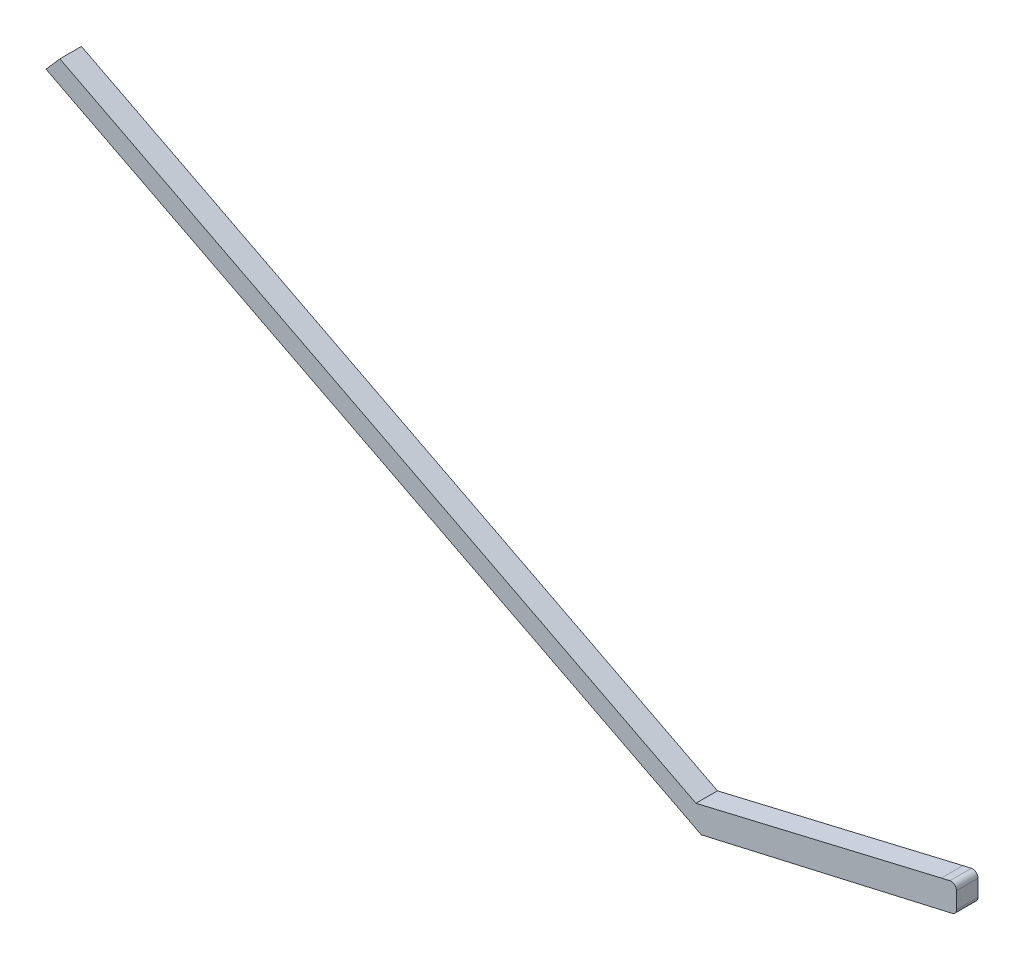
SolidWorks part; units mm, degrees
ref_plane "정면" through (0, 0, 0) normal (0, 0, 1) x (1, 0, 0)
ref_plane "윗면" through (0, 0, 0) normal (0, 1, 0) x (1, 0, 0)
ref_plane "우측면" through (0, 0, 0) normal (1, 0, 0) x (0, 0, -1)
sketch "스케치1" plane through (0, 0, 0) normal (0, 0, 1) x (1, 0, 0)
  line L0 (-103.3136, 14.4504) -> (-102.0239, 15.9264)
  line L2 (-18.8214, -9.3214) -> (-18.8214, -10.8602)
  line L3 (-20, -11.5262) -> (-42.5003, -16.6773)
  line L4 (-42.5003, -16.6773) -> (-103.3136, 14.4504)
  line L6 (-19.433, -8.834) -> (-20.2231, -9.0126)
  line L7 (-20, -11.5262) -> (-19.2098, -11.3476)
  line L8 (-102.0239, 15.9264) -> (-42.9983, -14.3898)
  line L9 (-42.9983, -14.3898) -> (-20.2231, -9.0126)
  arc A0 (-18.8214, -10.8602) -> (-19.2098, -11.3476) centre (-19.3214, -10.8602) cw
  arc A1 (-19.433, -8.834) -> (-18.8214, -9.3214) centre (-19.3214, -9.3214) cw
  dimension "D1" = 0.5
  dimension "D2" = 1.96
extrude "보스-돌출1" add sketch "스케치1" along normal blind 2
